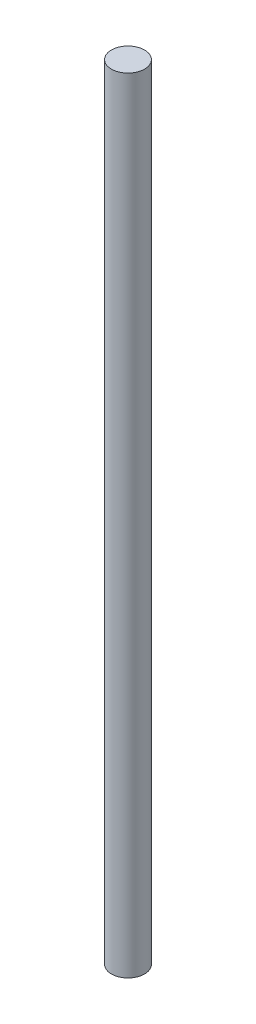
SolidWorks part; units mm, degrees
ref_plane "Front" through (0, 0, 0) normal (0, 0, 1) x (1, 0, 0)
ref_plane "Top" through (0, 0, 0) normal (0, 1, 0) x (1, 0, 0)
ref_plane "Right" through (0, 0, 0) normal (1, 0, 0) x (0, 0, -1)
sketch "Esboço1" plane through (0, 0, 0) normal (0, 1, 0) x (1, 0, 0)
  circle A0 centre (0, 0) radius 3.175
extrude "Ressalto-extrusão1" add sketch "Esboço1" along normal blind 150
